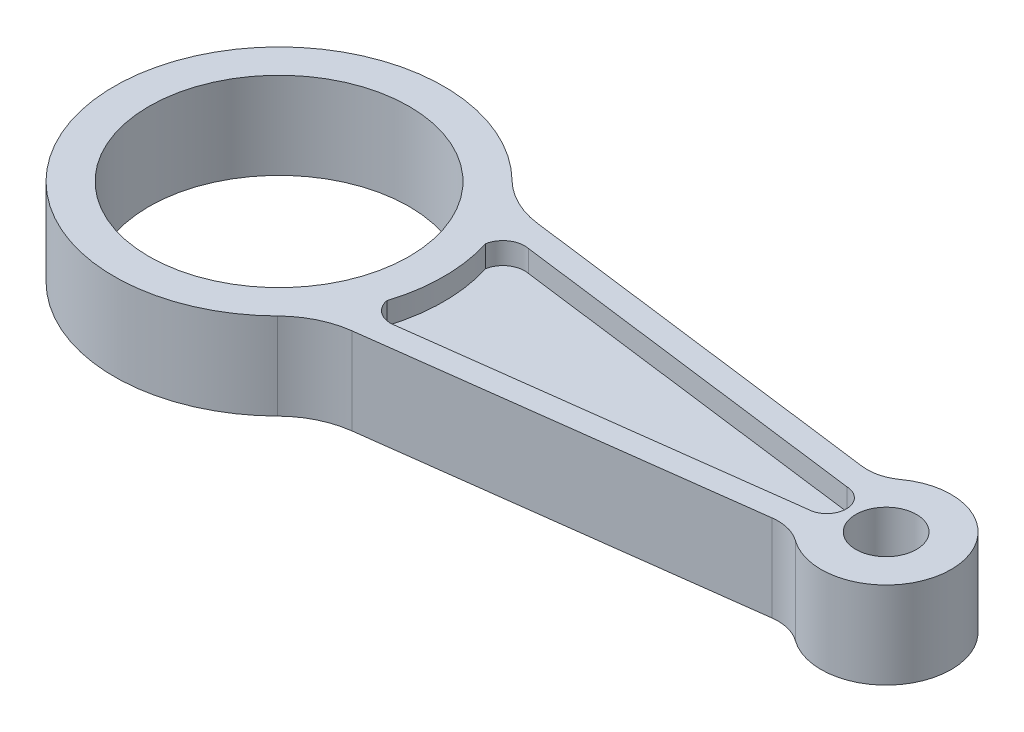
SolidWorks part; units mm, degrees
ref_plane "Front Plane" through (0, 0, 0) normal (0, 0, 1) x (1, 0, 0)
ref_plane "Top Plane" through (0, 0, 0) normal (0, 1, 0) x (1, 0, 0)
ref_plane "Right Plane" through (0, 0, 0) normal (1, 0, 0) x (0, 0, -1)
sketch "Sketch1" plane through (0, 0, 0) normal (0, 1, 0) x (1, 0, 0)
  line L0 (-37.6417, 0) -> (72.6239, 0) construction
  line L1 (72.6239, 0) -> (88.7296, 0) construction
  line L2 (30.7007, 22.3935) -> (128.6109, 9.7616)
  line L3 (30.7007, -22.3935) -> (128.6109, -9.7616)
  line L4 (88.7296, 0) -> (180.4322, 0) construction
  circle A0 centre (0, 0) radius 30
  arc A1 (30.7007, 22.3935) -> (30.7007, -22.3935) centre (0, 0) ccw
  arc A2 (128.6109, 9.7616) -> (128.6109, -9.7616) centre (140, 0) cw
  circle A3 centre (140, 0) radius 7
  dimension "D1" = 60
  dimension "D2" = 76
  dimension "D3" = 15
  dimension "D4" = 14
  dimension "D5" = 140
extrude "Boss-Extrude1" add sketch "Sketch1" along normal mid plane 20
fillet "Fillet1" radius 10 2 edges at (128.6109, 0, 9.7616) (128.6109, 0, -9.7616)
fillet "Fillet2" radius 20 2 edges at (30.7007, 0, 22.3935) (30.7007, 0, -22.3935)
sketch "Sketch2" plane through (0, 0, 0) normal (0, 1, 0) x (1, 0, 0)
  line L0 (0, 0) -> (195.9115, 0) construction
  line L1 (42.0978, -15.3775) -> (126.4183, -4.4989)
  line L2 (38.2026, -21.4256) -> (124.0791, -10.3463) construction
  line L3 (42.0978, 15.3775) -> (126.4183, 4.4989)
  line L4 (124.0791, 10.3463) -> (38.2026, 21.4256) construction
  arc A0 (36.2481, 11.4049) -> (36.2481, -11.4049) centre (0, 0) cw
  arc A3 (36.2481, 11.4049) -> (42.0978, 15.3775) centre (41.1593, 10.4664) cw
  arc A4 (36.2481, -11.4049) -> (42.0978, -15.3775) centre (41.1593, -10.4664) ccw
  circle A5 centre (0, 0) radius 30 construction
  arc A6 (126.4183, 4.4989) -> (126.4183, -4.4989) centre (126.3183, 0) cw
  point P18 (0, 0)
  dimension "D1" = 8
  dimension "D2" = 5
  dimension "D3" = 4.5
  dimension "D4" = 5.5
extrude "Cut-Extrude1" cut sketch "Sketch2" against normal blind 5 from offset 10
